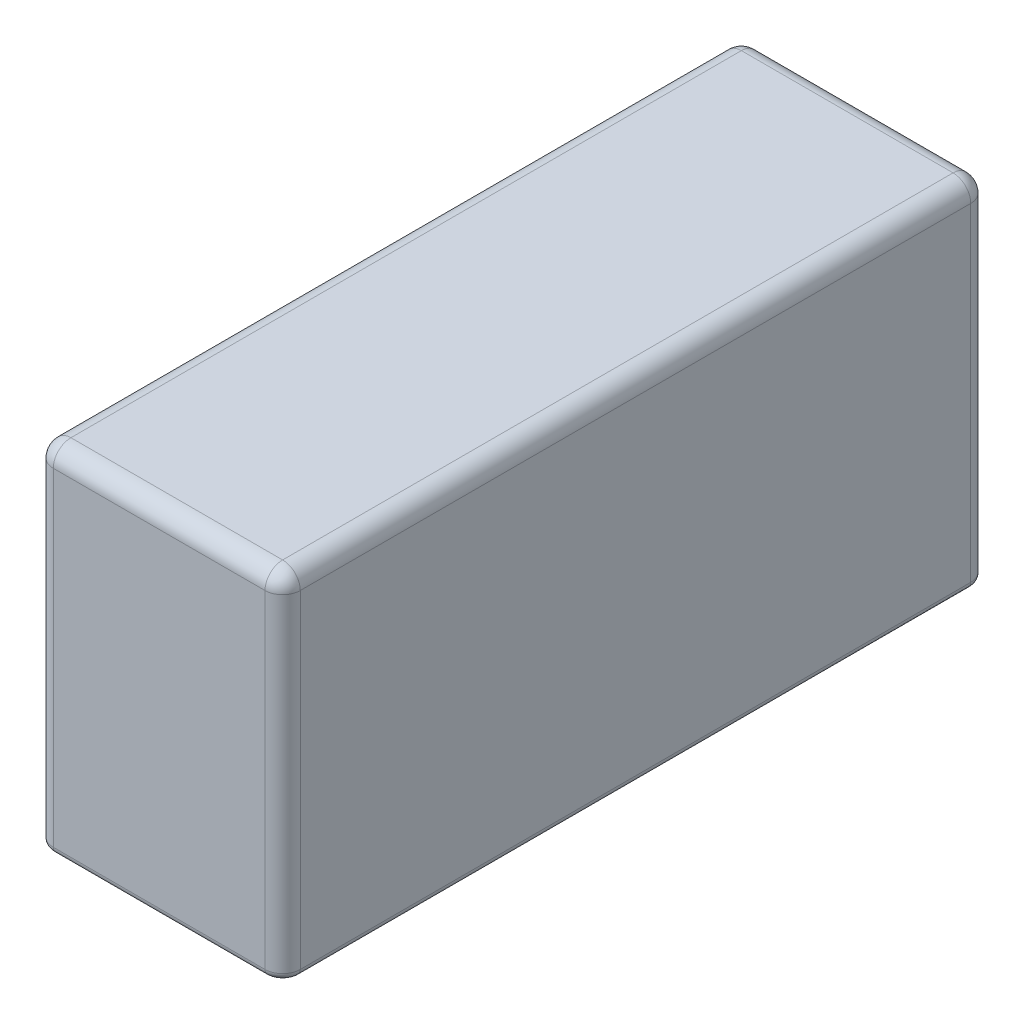
SolidWorks part; units mm, degrees
ref_plane "Front Plane" through (0, 0, 0) normal (0, 0, 1) x (1, 0, 0)
ref_plane "Top Plane" through (0, 0, 0) normal (0, 1, 0) x (1, 0, 0)
ref_plane "Right Plane" through (0, 0, 0) normal (1, 0, 0) x (0, 0, -1)
sketch "Sketch1" plane through (0, 0, 0) normal (0, 1, 0) x (1, 0, 0)
  line L1 (3.5, -10) -> (-3.5, -10)
  line L2 (3.5, -10) -> (3.5, 10)
  line L3 (3.5, 10) -> (-3.5, 10)
  line L4 (-3.5, -10) -> (-3.5, 10)
  line L5 (3.5, -10) -> (-3.5, 10) construction
  line L6 (3.5, 10) -> (-3.5, -10) construction
  point P0 (0, 0)
  dimension "D1" = 7
  dimension "D2" = 20
extrude "Boss-Extrude1" add sketch "Sketch1" along normal mid plane 10
fillet "Fillet2" radius 0.5 8 edges at (0, 5, -10) (3.5, 5, 0) (0, 5, 10) (-3.5, 5, 0) (-3.5, 0, -10) (-3.5, 0, 10) (3.5, 0, -10) (3.5, 0, 10)
fillet "Fillet3" radius 0.2 8 edges at (-3.3536, -5, 9.8536) (0, -5, 10) (3.3536, -5, 9.8536) (3.5, -5, 0) (3.3536, -5, -9.8536) (0, -5, -10) (-3.3536, -5, -9.8536) (-3.5, -5, 0)
